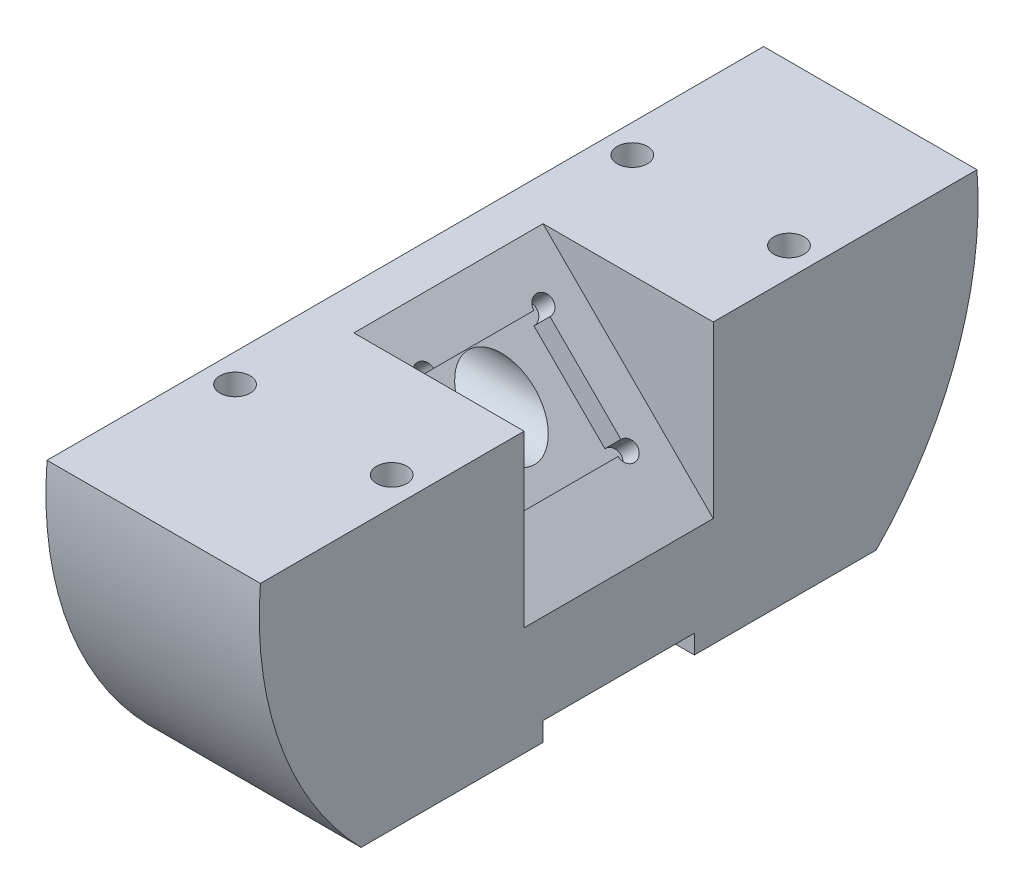
SolidWorks part; units mm, degrees
ref_plane "前视基准面" through (0, 0, 0) normal (0, 0, 1) x (1, 0, 0)
ref_plane "上视基准面" through (0, 0, 0) normal (0, 1, 0) x (1, 0, 0)
ref_plane "右视基准面" through (0, 0, 0) normal (1, 0, 0) x (0, 0, -1)
sketch "草图1" plane through (0, 0, 0) normal (1, 0, 0) x (0, 0, -1)
  circle A0 centre (0, 0) radius 19
  dimension "D1" = 38
extrude "凸台-拉伸1" add sketch "草图1" along normal blind 40
sketch "草图2" plane through (0, 0, 0) normal (0, 0, 1) x (1, 0, 0)
  line L0 (12.1861, 1.5) -> (14.4661, 1.5)
  line L2 (23.4661, -7.5) -> (23.4661, -14.75)
  line L3 (23.4661, -14.75) -> (12.1861, -14.75)
  line L4 (12.1861, -14.75) -> (12.1861, 1.5)
  line L6 (14.4661, 1.5) -> (23.4661, 1.5)
  line L7 (23.4661, 1.5) -> (23.4661, -7.5)
  line L9 (0, -19) -> (40, -19) construction
  dimension "D1" = 2.28
  dimension "D2" = 4.25
  dimension "D3" = 9
  dimension "D4" = 9
extrude "切除-拉伸1" cut sketch "草图2" against normal through all both and the other way through all flip side to cut
sketch "草图3" plane through (12.1861, 0, 0) normal (-1, 0, 0) x (0, 0, 1)
  circle A0 centre (0, -3) radius 1.75
  dimension "D1" = 3.5
  dimension "D2" = 3
extrude "切除-拉伸2" cut sketch "草图3" against normal blind 7.4
sketch "草图5" plane through (0, 0, 0) normal (0, 0, 1) x (1, 0, 0)
  line L0 (14.4661, 1.5) -> (23.4661, -7.5)
  line L1 (12.1861, 1.5) -> (23.4661, 1.5) construction
  line L2 (23.4661, -14.75) -> (23.4661, 1.5) construction
  line L3 (12.1861, 1.5) -> (14.4661, 1.5) construction
  line L5 (14.4661, 1.5) -> (23.4661, 1.5)
  line L6 (23.4661, 1.5) -> (23.4661, -7.5)
  dimension "D1" = 45
  dimension "D2" = 2.28
extrude "切除-拉伸4" cut sketch "草图5" against normal mid plane 10
sketch "草图6" plane through (7.983, 7.983, 0) normal (0.7071, 0.7071, 0) x (0, 0, -1)
  line L0 (-3.15, -11.8084) -> (3.15, -11.8084)
  line L1 (3.15, -11.8084) -> (3.15, -18.1084)
  line L2 (3.15, -18.1084) -> (-3.15, -18.1084)
  line L3 (-3.15, -18.1084) -> (-3.15, -11.8084)
  line L4 (-5, -9.1684) -> (-5, -21.8963) construction
  dimension "D1" = 6.3
  dimension "D2" = 6.3
  dimension "D3" = 1.85
extrude "切除-拉伸5" cut sketch "草图6" against normal blind 1.2
sketch "草图10" plane through (0, -14.75, 0) normal (0, -1, 0) x (1, 0, 0)
  line L4 (12.1861, -11.9765) -> (12.1861, 11.9765) construction
  line L5 (23.4661, -11.9765) -> (23.4661, 11.9765) construction
  circle A0 centre (13.6861, 10.5) radius 1.4
  circle A1 centre (21.9661, 10.5) radius 1.4
  circle A2 centre (13.6861, -10.5) radius 1.4
  circle A3 centre (21.9661, -10.5) radius 1.4
  dimension "D1" = 2.8
  dimension "D2" = 1.5
  dimension "D3" = 1.5
extrude "切除-拉伸8" cut sketch "草图10" against normal blind 13.7
sketch "草图11" plane through (0, -1.05, 0) normal (0, -1, 0) x (1, 0, 0)
  circle A0 centre (13.6861, 10.5) radius 0.8
  circle A1 centre (21.9661, 10.5) radius 0.8
  circle A2 centre (13.6861, -10.5) radius 0.8
  circle A3 centre (21.9661, -10.5) radius 0.8
  dimension "D1" = 1.6
extrude "切除-拉伸9" cut sketch "草图11" against normal up to next
sketch "草图12" plane through (23.4661, 0, 0) normal (1, 0, 0) x (0, 0, -1)
  line L0 (11.9765, -14.75) -> (-11.9765, -14.75) construction
  line L1 (-4, -14.75) -> (4, -14.75)
  line L2 (-4, -14.75) -> (-4, -12.25)
  line L3 (-4, -12.25) -> (4, -12.25)
  line L4 (4, -14.75) -> (4, -12.25)
  dimension "D1" = 8
  dimension "D2" = 2.5
  dimension "D3" = 4
extrude "切除-拉伸10" cut sketch "草图12" against normal through all
sketch "草图13" plane through (7.983, 7.983, 0) normal (0.7071, 0.7071, 0) x (0, 0, -1)
  circle A0 centre (-3.15, -11.8084) radius 0.5
  circle A1 centre (3.15, -11.8084) radius 0.5
  circle A2 centre (-3.15, -18.1084) radius 0.5
  circle A3 centre (3.15, -18.1084) radius 0.5
  dimension "D1" = 1
extrude "切除-拉伸11" cut sketch "草图13" against normal blind 1.2
sketch "草图14" plane through (12.1861, 0, 0) normal (-1, 0, 0) x (0, 0, 1)
  line L0 (11.1835, -13.25) -> (12.1835, -13.25) construction
  line L1 (-15.7199, -13.25) -> (15.4684, -13.25)
  line L2 (-15.7199, -13.25) -> (-15.7199, -16.4435)
  line L3 (-15.7199, -16.4435) -> (15.4684, -16.4435)
  line L4 (15.4684, -13.25) -> (15.4684, -16.4435)
extrude "切除-拉伸12" cut sketch "草图14" against normal through all both and the other way through all
